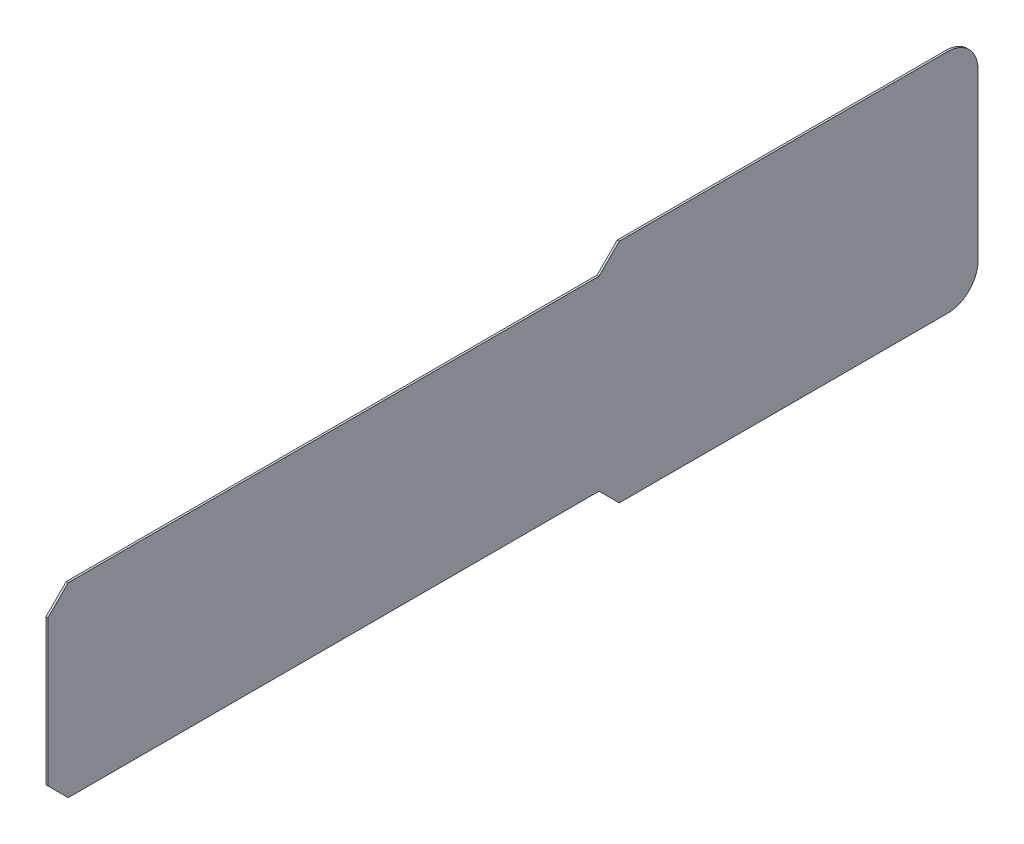
SolidWorks part; units mm, degrees
ref_plane "Front Plane" through (0, 0, 0) normal (0, 0, 1) x (1, 0, 0)
ref_plane "Top Plane" through (0, 0, 0) normal (0, 1, 0) x (1, 0, 0)
ref_plane "Right Plane" through (0, 0, 0) normal (1, 0, 0) x (0, 0, -1)
sketch "Sketch2" plane through (0, 0, 0) normal (-1, 0, 0) x (0, 1, 0)
  line L1 (-55.0231, 28.6615) -> (-32.6031, 28.6615)
  line L2 (-55.0231, 28.6615) -> (-55.0231, -63.3385)
  line L3 (-55.0231, -63.3385) -> (-32.6031, -63.3385)
  line L4 (-32.6031, 28.6615) -> (-32.6031, -63.3385)
  dimension "D1" = 92
  dimension "D2" = 22.42
extrude "Boss-Extrude2" add sketch "Sketch2" along normal blind 0.2 contours L2 L3 L4 L1
fillet "Fillet4" radius 3 1 edges at (-0.1, -55.0231, -28.6615)
fillet "Fillet7" radius 3 1 edges at (-0.1, -32.6031, -28.6615)
sketch "Sketch4" plane through (-0.2, 0, 0) normal (-1, 0, 0) x (0, 1, 0)
  line L0 (-55.0231, 25.6615) -> (-55.0231, -63.3385) construction
  line L1 (-55.0231, -8.8285) -> (-53.0231, -8.8285)
  line L2 (-55.0231, -8.8285) -> (-55.0231, -63.3385)
  line L3 (-55.0231, -63.3385) -> (-53.0231, -63.3385)
  line L4 (-53.0231, -8.8285) -> (-53.0231, -63.3385)
  line L5 (-55.0231, -63.3385) -> (-32.6031, -63.3385) construction
  dimension "D1" = 2
  dimension "D2" = 54.51
extrude "Cut-Extrude1" cut sketch "Sketch4" against normal blind 0.2
sketch "Sketch5" plane through (-0.2, 0, 0) normal (-1, 0, 0) x (0, 1, 0)
  line L1 (-34.6031, -8.8285) -> (-32.6031, -8.8285)
  line L2 (-34.6031, -8.8285) -> (-34.6031, -63.3385)
  line L3 (-34.6031, -63.3385) -> (-32.6031, -63.3385)
  line L4 (-32.6031, -8.8285) -> (-32.6031, -63.3385)
  dimension "D1" = 2
  dimension "D2" = 54.51
extrude "Cut-Extrude2" cut sketch "Sketch5" against normal blind 0.2
sketch "Sketch6" plane through (-0.2, 0, 0) normal (-1, 0, 0) x (0, 1, 0)
  line L0 (-53.0231, -63.3385) -> (-53.0231, -61.3385)
  line L1 (-53.0231, -63.3385) -> (-53.0231, -8.8285) construction
  line L2 (-53.0231, -63.3385) -> (-51.0231, -63.3385)
  line L3 (-53.0231, -63.3385) -> (-34.6031, -63.3385) construction
  line L4 (-53.0231, -61.3385) -> (-51.0231, -63.3385)
extrude "Cut-Extrude3" cut sketch "Sketch6" against normal blind 0.2
sketch "Sketch7" plane through (-0.2, 0, 0) normal (-1, 0, 0) x (0, 1, 0)
  line L0 (-34.6031, -63.3385) -> (-34.6031, -61.3385)
  line L1 (-34.6031, -8.8285) -> (-34.6031, -63.3385) construction
  line L2 (-34.6031, -63.3385) -> (-36.6031, -63.3385)
  line L3 (-51.0231, -63.3385) -> (-34.6031, -63.3385) construction
  line L4 (-34.6031, -61.3385) -> (-36.6031, -63.3385)
extrude "Cut-Extrude4" cut sketch "Sketch7" against normal blind 0.2
sketch "Sketch8" plane through (-0.2, 0, 0) normal (-1, 0, 0) x (0, 1, 0)
  line L0 (-53.0231, -8.8285) -> (-55.0231, -8.8285)
  line L2 (-55.0231, -8.8285) -> (-55.0231, -6.8285)
  line L3 (-55.0231, 25.6615) -> (-55.0231, -8.8285) construction
  line L4 (-55.0231, -6.8285) -> (-53.0231, -8.8285)
extrude "Cut-Extrude7" cut sketch "Sketch8" against normal blind 0.2
sketch "Sketch9" plane through (-0.2, 0, 0) normal (-1, 0, 0) x (0, 1, 0)
  line L0 (-34.6031, -8.8285) -> (-32.6031, -8.8285)
  line L1 (-32.6031, -8.8285) -> (-34.6031, -8.8285) construction
  line L2 (-32.6031, -8.8285) -> (-32.6031, -6.8285)
  line L3 (-32.6031, 25.6615) -> (-32.6031, -8.8285) construction
  line L4 (-32.6031, -6.8285) -> (-34.6031, -8.8285)
extrude "Cut-Extrude8" cut sketch "Sketch9" against normal blind 0.2
